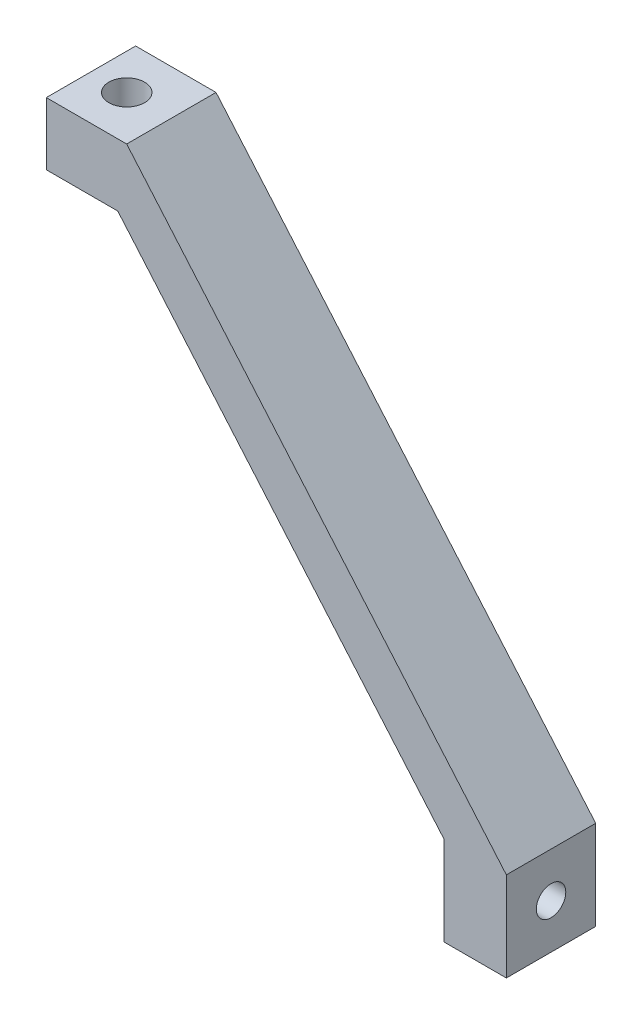
SolidWorks part; units mm, degrees
ref_plane "Alzado" through (0, 0, 0) normal (0, 0, 1) x (1, 0, 0)
ref_plane "Planta" through (0, 0, 0) normal (0, 1, 0) x (1, 0, 0)
ref_plane "Vista lateral" through (0, 0, 0) normal (1, 0, 0) x (0, 0, -1)
sketch "Croquis1" plane through (0, 0, 0) normal (0, 0, 1) x (1, 0, 0)
  line L0 (7, 0) -> (-35.5, 49.6)
  line L1 (0, 0) -> (7, 0)
  line L2 (0, 0) -> (0, -10)
  line L3 (0, -10) -> (7, -10)
  line L4 (7, 0) -> (7, -10)
  line L9 (0, 0) -> (-30, 0) construction
  line L22 (-35.5, 49.6) -> (-44.5, 49.6)
  line L23 (-35.5, 49.6) -> (-35.5, 42.6)
  line L24 (-35.5, 42.6) -> (-44.5, 42.6)
  line L25 (-44.5, 49.6) -> (-44.5, 42.6)
  line L26 (0, 0) -> (-36.4997, 42.6)
  dimension "D1" = 10
  dimension "D2" = 7
  dimension "D3" = 49.408
  dimension "D4" = 49.41
extrude "Saliente-Extruir1" add sketch "Croquis1" along normal blind 10
sketch "Croquis3" plane through (0, 49.6, 0) normal (0, 1, 0) x (1, 0, 0)
  line L0 (-44.5, -5) -> (-40.5, -5) construction
  line L1 (-44.5, -10) -> (-44.5, 0) construction
  circle A0 centre (-40.5, -5) radius 2
extrude "Cortar-Extruir2" cut sketch "Croquis3" against normal blind 10
sketch "Croquis4" plane through (7, 0, 0) normal (1, 0, 0) x (0, 0, -1)
  line L0 (-10, 0) -> (0, -10) construction
  circle A0 centre (-5, -5) radius 1.65
  dimension "D1" = 3.3
extrude "Cortar-Extruir3" cut sketch "Croquis4" against normal blind 10
